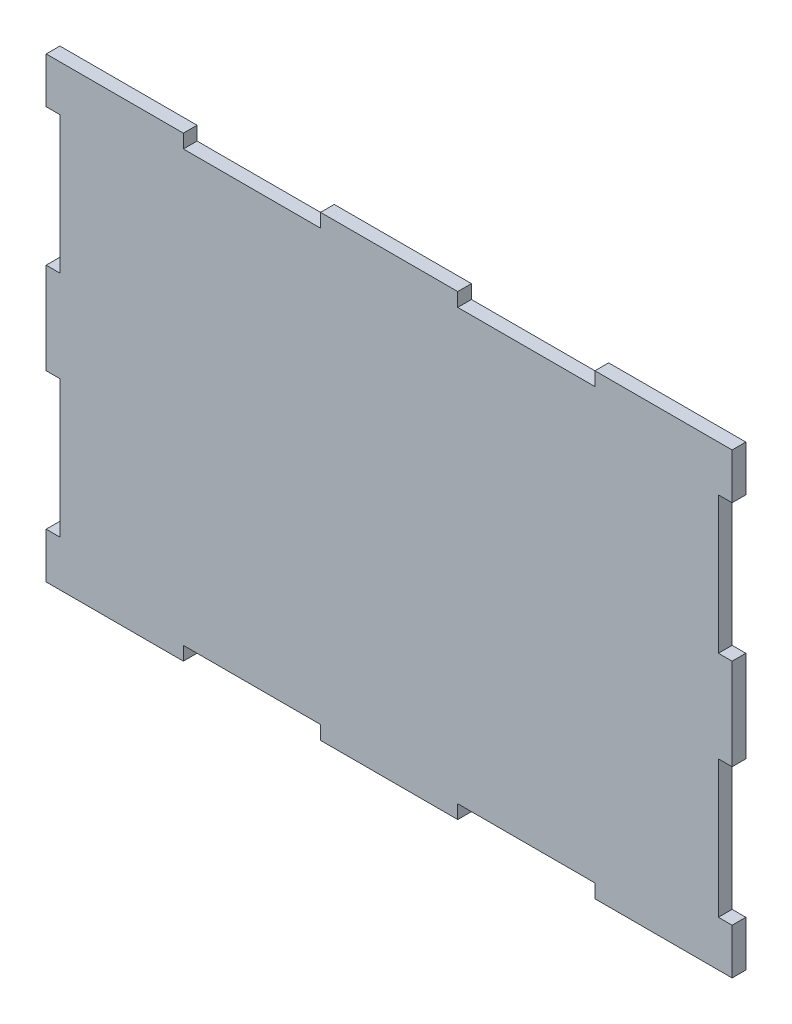
SolidWorks part; units mm, degrees
ref_plane "Plan de face" through (0, 0, 0) normal (0, 0, 1) x (1, 0, 0)
ref_plane "Plan de dessus" through (0, 0, 0) normal (0, 1, 0) x (1, 0, 0)
ref_plane "Plan de droite" through (0, 0, 0) normal (1, 0, 0) x (0, 0, -1)
sketch "Esquisse1" plane through (0, 0, 0) normal (0, 0, 1) x (1, 0, 0)
  line L0 (18.416, 28.0197) -> (48.416, 28.0197)
  line L1 (-41.584, 28.0197) -> (-11.584, 28.0197)
  line L2 (-41.584, 28.0197) -> (-41.584, 18.0197)
  line L3 (-41.584, -71.9803) -> (-11.584, -71.9803)
  line L4 (108.416, 28.0197) -> (108.416, 18.0197)
  line L5 (78.416, 28.0197) -> (108.416, 28.0197)
  line L6 (-11.584, 28.0197) -> (-11.584, 25.0197)
  line L7 (-11.584, 25.0197) -> (18.416, 25.0197)
  line L8 (18.416, 28.0197) -> (18.416, 25.0197)
  line L9 (18.416, -71.9803) -> (48.416, -71.9803)
  line L10 (48.416, 28.0197) -> (48.416, 25.0197)
  line L11 (48.416, 25.0197) -> (78.416, 25.0197)
  line L12 (78.416, 28.0197) -> (78.416, 25.0197)
  line L13 (78.416, -71.9803) -> (108.416, -71.9803)
  line L14 (-11.584, -71.9803) -> (-11.584, -68.9803)
  line L15 (-11.584, -68.9803) -> (18.416, -68.9803)
  line L16 (18.416, -71.9803) -> (18.416, -68.9803)
  line L17 (48.416, -68.9803) -> (78.416, -68.9803)
  line L18 (48.416, -68.9803) -> (48.416, -71.9803)
  line L19 (-41.584, -11.9803) -> (-41.584, -31.9803)
  line L20 (78.416, -68.9803) -> (78.416, -71.9803)
  line L21 (108.416, 18.0197) -> (105.416, 18.0197)
  line L23 (108.416, -11.9803) -> (105.416, -11.9803)
  line L24 (105.416, 18.0197) -> (105.416, -11.9803)
  line L25 (108.416, -31.9803) -> (105.416, -31.9803)
  line L26 (108.416, -11.9803) -> (108.416, -31.9803)
  line L27 (108.416, -61.9803) -> (105.416, -61.9803)
  line L28 (105.416, -31.9803) -> (105.416, -61.9803)
  line L29 (-41.584, 18.0197) -> (-38.584, 18.0197)
  line L30 (-41.584, -61.9803) -> (-41.584, -71.9803)
  line L31 (-41.584, -11.9803) -> (-38.584, -11.9803)
  line L32 (-38.584, 18.0197) -> (-38.584, -11.9803)
  line L33 (-38.584, -31.9803) -> (-41.584, -31.9803)
  line L34 (-38.584, -31.9803) -> (-38.584, -61.9803)
  line L35 (-38.584, -61.9803) -> (-41.584, -61.9803)
  line L36 (108.416, -61.9803) -> (108.416, -71.9803)
  dimension "D1" = 150
  dimension "D2" = 100
  dimension "D3" = 30
  dimension "D4" = 30
  dimension "D5" = 3
  dimension "D6" = 30
  dimension "D7" = 30
  dimension "D8" = 3
  dimension "D9" = 30
  dimension "D10" = 30
  dimension "D11" = 3
  dimension "D12" = 30
  dimension "D13" = 30
  dimension "D14" = 3
  dimension "D15" = 10
  dimension "D16" = 30
  dimension "D17" = 30
  dimension "D18" = 30
  dimension "D19" = 30
  dimension "D20" = 3
  dimension "D21" = 3
  dimension "D22" = 3
  dimension "D23" = 10
  dimension "D24" = 10
  dimension "D25" = 10
  dimension "D26" = 20
extrude "Boss.-Extru.1" add sketch "Esquisse1" along normal blind 3
